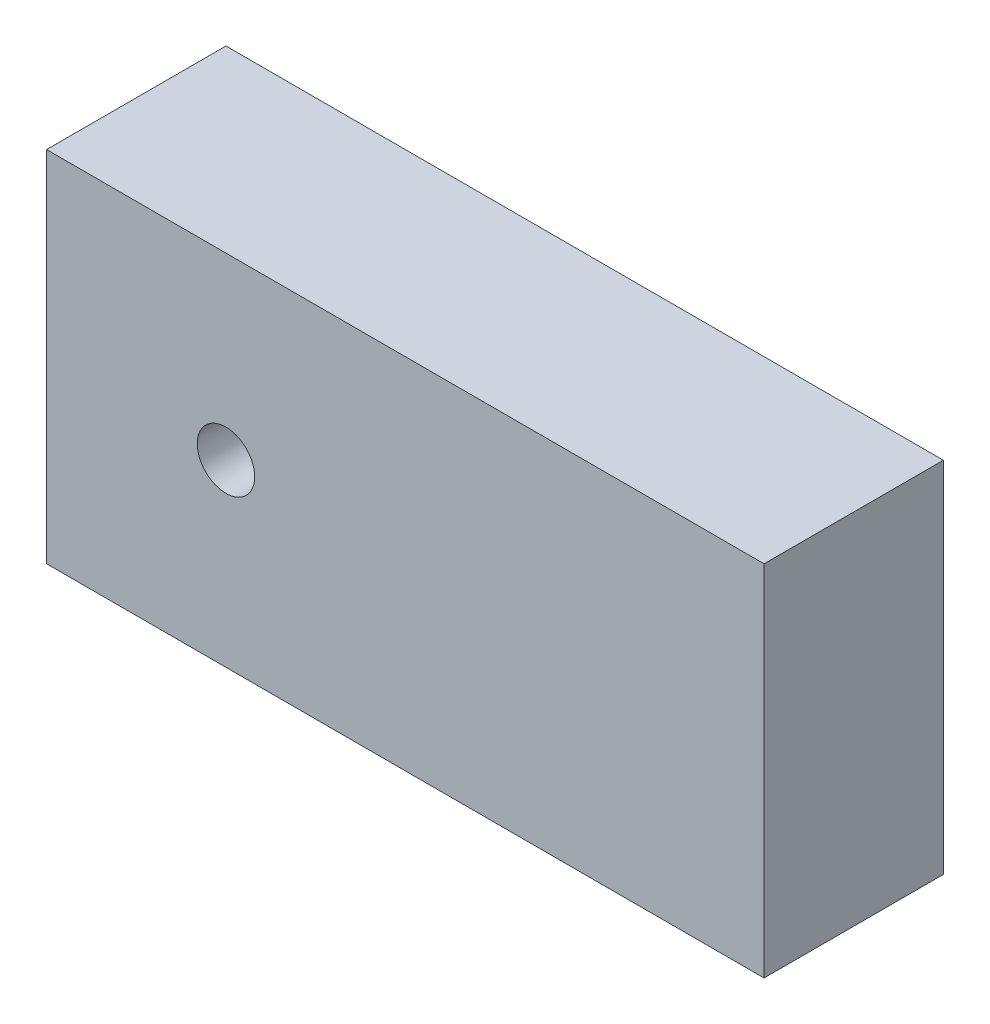
SolidWorks part; units mm, degrees
ref_plane "前视基准面" through (0, 0, 0) normal (0, 0, 1) x (1, 0, 0)
ref_plane "上视基准面" through (0, 0, 0) normal (0, 1, 0) x (1, 0, 0)
ref_plane "右视基准面" through (0, 0, 0) normal (1, 0, 0) x (0, 0, -1)
other "Configuration Table"
sketch "草图1" plane through (0, 0, 0) normal (0, 0, 1) x (1, 0, 0)
  line L1 (0, 0) -> (40, 0)
  line L2 (0, 0) -> (0, 20)
  line L3 (0, 20) -> (40, 20)
  line L4 (40, 0) -> (40, 20)
  circle A0 centre (10, 10) radius 1.6
  dimension "D3" = 3.2
  dimension "D1" = 40
  dimension "D2" = 20
extrude "凸台-拉伸1" add sketch "草图1" along normal blind 10
